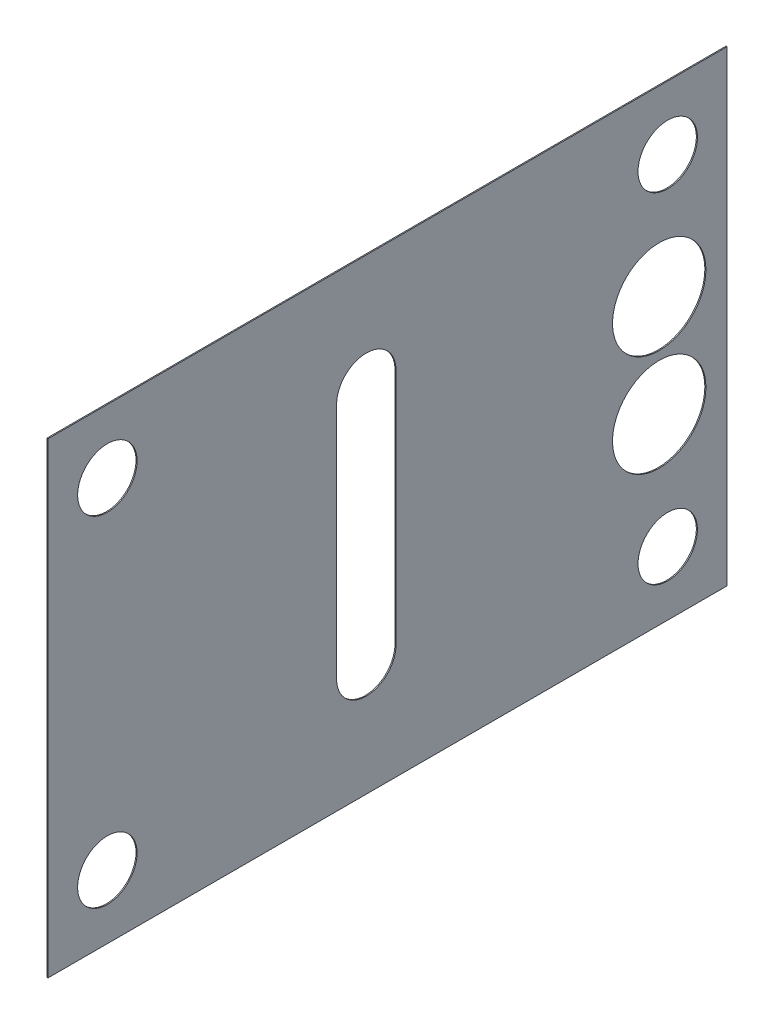
SolidWorks part; units mm, degrees
material "Low Carbon Steel"
ref_plane "Front Plane" through (0, 0, 0) normal (0, 0, 1) x (1, 0, 0)
ref_plane "Top Plane" through (0, 0, 0) normal (0, 1, 0) x (1, 0, 0)
ref_plane "Right Plane" through (0, 0, 0) normal (1, 0, 0) x (0, 0, -1)
sketch "Sketch1" plane through (0, 0, 0) normal (1, 0, 0) x (0, 0, -1)
  line L0 (-80, -55) -> (80, 55) construction
  line L1 (-80, 55) -> (80, 55)
  line L2 (-80, 55) -> (-80, -55)
  line L3 (-80, -55) -> (80, -55)
  line L4 (80, 55) -> (80, -55)
  dimension "D1" = 160
  dimension "D2" = 110
extrude "Boss-Extrude1" add sketch "Sketch1" along normal blind 0.254
hole_wizard "M12 Clearance Hole1" positions "Sketch2" profile "Sketch3" hole size "M12" standard "Peddi DIN" end condition through all
sketch "Sketch2" plane through (0.254, 0, 0) normal (1, 0, 0) x (0, 0, -1)
  line L0 (-66, 40) -> (66, 40) construction
  line L1 (66, 40) -> (66, -40) construction
  line L2 (66, -40) -> (-66, -40) construction
  line L3 (-66, -40) -> (66, 40) construction
  point P0 (-66, 40)
  point P2 (66, 40)
  point P4 (66, -40)
  point P6 (-66, -40)
  dimension "D1" = 80
  dimension "D2" = 132
sketch "Sketch3" plane through (0.254, 40, 66) normal (0, 1, 0) x (0, 0, -1)
  line L0 (0, 0) -> (0, 0.254)
  line L1 (0, 0.254) -> (7, 0.254)
  line L2 (7, 0.254) -> (7, 0)
  line L5 (7, 0) -> (0, 0)
  line L11 (0, -6.35) -> (0, 107.95) construction
  dimension "Thru Hole Dia." = 14
  dimension "Thru Hole Depth" = 0.254
sketch "Sketch4" plane through (0.254, 0, 0) normal (1, 0, 0) x (0, 0, -1)
  line L0 (-5, 28) -> (-5, -28) construction
  line L1 (2, 28) -> (2, -28)
  line L2 (-12, 28) -> (-12, -28)
  line L3 (-5, 0) -> (0, 0) construction
  arc A0 (2, 28) -> (-12, 28) centre (-5, 28) ccw
  arc A1 (-12, -28) -> (2, -28) centre (-5, -28) ccw
  circle A2 centre (66, 40) radius 7 construction
  point P2 (-5, 0)
  dimension "D3" = 71
  dimension "D1" = 14
  dimension "D2" = 56
extrude "Cut-Extrude1" cut sketch "Sketch4" against normal through all
hole_wizard "M20 Clearance Hole1" positions "Sketch5" profile "Sketch6" hole size "M20" standard "Peddi DIN" end condition through all
sketch "Sketch5" plane through (0.254, 0, 0) normal (1, 0, 0) x (0, 0, -1)
  line L0 (64, 12) -> (64, -12) construction
  line L2 (0, 0) -> (64, 0) construction
  circle A0 centre (66, 40) radius 7 construction
  point P0 (64, 12)
  point P5 (64, -12)
  dimension "D2" = 2
  dimension "D1" = 28
sketch "Sketch6" plane through (0.254, 12, -64) normal (0, 1, 0) x (0, 0, -1)
  line L0 (0, 0) -> (0, 0.254)
  line L1 (0, 0.254) -> (11, 0.254)
  line L2 (11, 0.254) -> (11, 0)
  line L5 (11, 0) -> (0, 0)
  line L11 (0, -6.35) -> (0, 107.95) construction
  dimension "Thru Hole Dia." = 22
  dimension "Thru Hole Depth" = 0.254
other "Freeze***"
